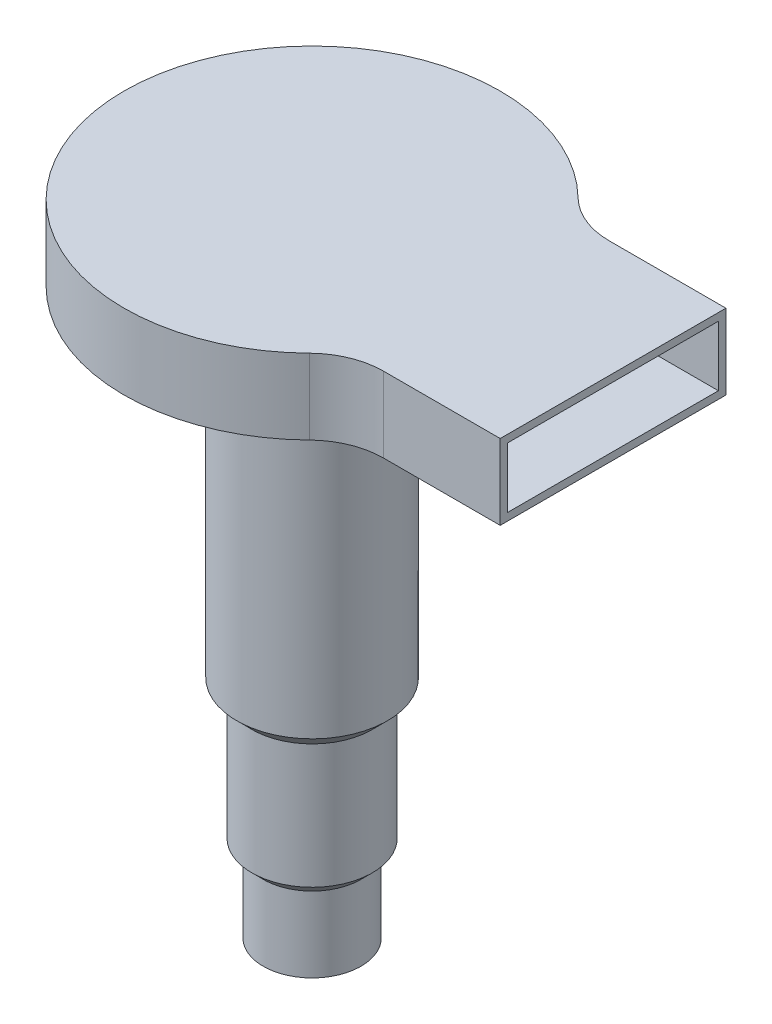
SolidWorks part; units mm, degrees
material "PE High Density"
ref_plane "Front Plane" through (0, 0, 0) normal (0, 0, 1) x (1, 0, 0)
ref_plane "Top Plane" through (0, 0, 0) normal (0, 1, 0) x (1, 0, 0)
ref_plane "Right Plane" through (0, 0, 0) normal (1, 0, 0) x (0, 0, -1)
sketch "Sketch1" plane through (0, 0, 0) normal (1, 0, 0) x (0, 0, -1)
  line L0 (0, 0) -> (0, 98.6007) construction
  line L2 (5, 0) -> (6.5, 0)
  line L3 (6.5, 0) -> (6.5, 10)
  line L4 (6.5, 10) -> (8, 11.5)
  line L5 (8, 11.5) -> (8, 28)
  line L6 (8, 28) -> (10, 30)
  line L7 (10, 30) -> (10, 70)
  line L8 (10, 70) -> (12, 70)
  line L9 (12, 70) -> (12, 75)
  line L10 (12, 75) -> (0, 75)
  line L11 (5, 0) -> (5, 35)
  line L12 (5, 35) -> (0, 35)
  line L13 (0, 35) -> (0, 75)
  dimension "D1" = 5
  dimension "D2" = 35
  dimension "D3" = 70
  dimension "D4" = 5
  dimension "D5" = 10
  dimension "D6" = 8
  dimension "D7" = 12
  dimension "D8" = 40
  dimension "D9" = 6.5
  dimension "D10" = 45
  dimension "D11" = 10
revolve "Revolve1" add sketch "Sketch1" angle 360 about L0
sketch "Sketch2" plane through (0, 75, 0) normal (0, 1, 0) x (1, 0, 0)
  line L1 (24.4949, 15) -> (40, 15)
  line L3 (24.4949, -15) -> (40, -15)
  line L4 (40, 15) -> (40, -15)
  arc A0 (17.4964, 17.8571) -> (17.4964, -17.8571) centre (0, 0) ccw
  arc A1 (17.4964, -17.8571) -> (24.4949, -15) centre (24.4949, -25) cw
  arc A2 (24.4949, 15) -> (17.4964, 17.8571) centre (24.4949, 25) cw
  point P1 (40, 0)
  dimension "D1" = 25
  dimension "D4" = 10
  dimension "D2" = 30
  dimension "D3" = 40
extrude "Boss-Extrude1" add sketch "Sketch2" along normal blind 10 separate body
shell "Shell1" thickness 1
combine bodies "Combine1" operation type add bodies to combine 102 101
